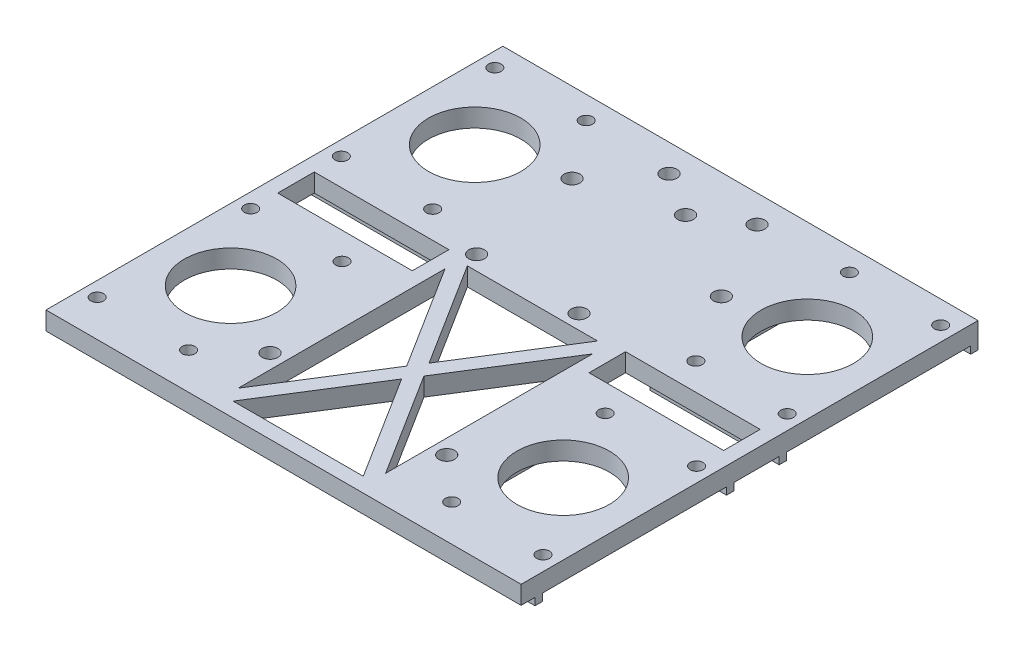
SolidWorks part; units mm, degrees
ref_plane "Front Plane" through (0, 0, 0) normal (0, 0, 1) x (1, 0, 0)
ref_plane "Top Plane" through (0, 0, 0) normal (0, 1, 0) x (1, 0, 0)
ref_plane "Right Plane" through (0, 0, 0) normal (1, 0, 0) x (0, 0, -1)
sketch "Sketch1" plane through (0, 0, 0) normal (0, 1, 0) x (1, 0, 0)
  line L1 (-65, 62.5) -> (65, 62.5)
  line L2 (-65, 62.5) -> (-65, -62.5)
  line L3 (-65, -62.5) -> (65, -62.5)
  line L4 (65, 62.5) -> (65, -62.5)
  line L5 (-65, 62.5) -> (65, -62.5) construction
  line L6 (-65, -62.5) -> (65, 62.5) construction
  point P0 (0, 0)
  dimension "D1" = 130
  dimension "D2" = 125
extrude "Boss-Extrude1" add sketch "Sketch1" along normal blind 5
sketch "Sketch2" plane through (0, 5, 0) normal (0, 1, 0) x (1, 0, 0)
  line L1 (-65, -62.5) -> (65, -62.5) construction
  line L2 (-65, 62.5) -> (-65, -62.5) construction
  circle A0 centre (-61, -52.5) radius 1.75
  circle A1 centre (-36, -52.5) radius 1.75
  circle A2 centre (-36, -10.5) radius 1.75
  circle A3 centre (-61, -10.5) radius 1.75
  circle A4 centre (-45.5, -31.5) radius 12.65
  dimension "D2" = 25.3
  dimension "D7" = 3.5
  dimension "D8" = 3.5
  dimension "D9" = 3.5
  dimension "D10" = 3.5
  dimension "D1" = 19.5
  dimension "D3" = 31
  dimension "D4" = 4
  dimension "D5" = 10
  dimension "D6" = 10
  dimension "D11" = 4
  dimension "D12" = 42
  dimension "D13" = 42
  dimension "D14" = 25
  dimension "D15" = 25
extrude "Cut-Extrude1" cut sketch "Sketch2" against normal blind 10
ref_plane "Plane1" through (0, 0, 0) normal (-1, 0, 0) x (0, 0, 1)
ref_plane "Plane2" through (0, 0, 0) normal (0, 0, 1) x (1, 0, 0)
mirror "Mirror3" about plane through (0, 0, 0) normal (-1, 0, 0) of "Cut-Extrude1"
sketch "Sketch4" plane through (0, 5, 0) normal (0, 1, 0) x (1, 0, 0)
  line L0 (0, 62.5) -> (0, 47.5) construction
  line L1 (65, 62.5) -> (-65, 62.5) construction
  line L2 (-12.0498, 55) -> (12.0498, 55) construction
  circle A0 centre (0, 47.5) radius 2.15
  circle A1 centre (12.0498, 55) radius 2.15
  circle A2 centre (-12.0498, 55) radius 2.15
  point P9 (0, 55)
  dimension "D2" = 4.3
  dimension "D3" = 4.3
  dimension "D4" = 4.3
  dimension "D1" = 15
  dimension "D5" = 24.0996
extrude "Cut-Extrude3" cut sketch "Sketch4" against normal blind 10
sketch "Sketch5" plane through (0, 0, 0) normal (0, -1, 0) x (1, 0, 0)
  line L0 (-58.15, 31.5) -> (-65, 31.5) construction
  line L1 (-65, -62.5) -> (-65, 62.5) construction
  line L2 (-65, 56.7) -> (-65, 6.3)
  line L3 (-65, 56.7) -> (-31.6, 56.7)
  line L4 (-31.6, 56.7) -> (-31.6, 6.3)
  line L5 (-31.6, 6.3) -> (-65, 6.3)
  line L6 (-65, 58.7) -> (-29.6, 58.7)
  line L7 (-29.6, 58.7) -> (-29.6, 4.3)
  line L8 (-29.6, 4.3) -> (-65, 4.3)
  line L9 (-65, 4.3) -> (-65, 6.3)
  line L10 (-65, 58.7) -> (-65, 56.7)
  circle A0 centre (-45.5, 31.5) radius 12.65 construction
  point P10 (-65, 31.5)
  line M39 (-65, 62.5) -> (-65, -62.5)
  dimension "D1" = 50.4
  dimension "D2" = 33.4
  dimension "D3" = 2
  dimension "D4" = 2
  dimension "D5" = 2
extrude "Boss-Extrude2" add sketch "Sketch5" along normal blind 2 contours L8 L7 L6 L3 L4 L5 M39
mirror "Mirror5" about plane through (0, 0, 0) normal (-1, 0, 0) of "Boss-Extrude2"
ref_plane "Plane3" through (0, 0, 0) normal (0, 0, 1) x (1, 0, 0)
ref_plane "Plane4" through (0, 0, -1.9) normal (0, 0, 1) x (1, 0, 0)
mirror "Mirror7" about plane through (0, 0, -1.9) normal (0, 0, 1) of "Mirror5", "Boss-Extrude2", "Mirror3", "Cut-Extrude1"
ref_plane "Plane5" through (0, 0, 0) normal (0, -1, 0) x (-1, 0, 0)
sketch "Sketch10" plane through (0, 0, 0) normal (0, -1, 0) x (-1, 0, 0)
  circle A0 centre (-24.17, -42.03) radius 2.15
  circle A1 centre (24.17, -42.03) radius 2.15
  circle A2 centre (-8.73, 9.6) radius 2.15
  circle A3 centre (19.29, 9.6) radius 2.15
  circle A4 centre (-24.17, 33.11) radius 2.15
  circle A5 centre (24.17, 40.6) radius 2.15
  dimension "D1" = 4.3
  dimension "D6" = 4.3
  dimension "D7" = 4.3
  dimension "D10" = 4.3
  dimension "D11" = 4.3
  dimension "D12" = 4.3
extrude "Cut-Extrude8" cut sketch "Sketch10" against normal through all
sketch "Sketch11" plane through (0, 0, 0) normal (0, -1, 0) x (1, 0, 0)
  circle A0 centre (-12.0498, -55) radius 2.65
  circle A1 centre (0, -47.5) radius 2.65
  circle A2 centre (12.0498, -55) radius 2.65
  circle A3 centre (-24.17, -40.6) radius 2.65
  circle A4 centre (24.17, -33.11) radius 2.65
  circle A5 centre (8.73, -9.6) radius 2.65
  circle A6 centre (-19.29, -9.6) radius 2.65
  circle A7 centre (-24.17, 42.03) radius 2.65
  circle A8 centre (24.17, 42.03) radius 2.65
  circle A9 centre (-61, -14.3) radius 2.65
  circle A10 centre (-36, -14.3) radius 2.65
  circle A11 centre (-61, -56.3) radius 2.65
  circle A12 centre (-36, -56.3) radius 2.65
  circle A13 centre (36, -56.3) radius 2.65
  circle A14 centre (61, -56.3) radius 2.65
  circle A15 centre (36, -14.3) radius 2.65
  circle A16 centre (61, -14.3) radius 2.65
  circle A17 centre (36, 10.5) radius 2.65
  circle A18 centre (61, 10.5) radius 2.65
  circle A19 centre (61, 52.5) radius 2.65
  circle A20 centre (36, 52.5) radius 2.65
  circle A21 centre (-36, 52.5) radius 2.65
  circle A22 centre (-36, 10.5) radius 2.65
  circle A23 centre (-61, 10.5) radius 2.65
  circle A24 centre (-61, 52.5) radius 2.65
  dimension "D1" = 5.3
  dimension "D2" = 5.3
  dimension "D3" = 5.3
  dimension "D4" = 5.3
  dimension "D5" = 5.3
  dimension "D6" = 5.3
  dimension "D7" = 5.3
  dimension "D8" = 5.3
  dimension "D9" = 5.3
  dimension "D10" = 5.3
  dimension "D11" = 5.3
  dimension "D12" = 5.3
  dimension "D13" = 5.3
  dimension "D14" = 5.3
  dimension "D15" = 5.3
  dimension "D16" = 5.3
  dimension "D17" = 5.3
  dimension "D18" = 5.3
  dimension "D19" = 5.3
  dimension "D20" = 5.3
  dimension "D21" = 5.3
  dimension "D22" = 5.3
  dimension "D23" = 5.3
  dimension "D24" = 5.3
  dimension "D25" = 5.3
extrude "Cut-Extrude9" cut sketch "Sketch11" against normal blind 0.5
sketch "Sketch12" plane through (0, 5, 0) normal (0, 1, 0) x (1, 0, 0)
  line L0 (-65, -62.5) -> (65, -62.5) construction
  line L1 (-20.17, 5.6) -> (20.17, 5.6)
  line L2 (-20.17, 5.6) -> (-20.17, -58.5)
  line L3 (-20.17, -58.5) -> (20.17, -58.5)
  line L4 (20.17, 5.6) -> (20.17, -58.5)
  line L5 (-20.17, 5.6) -> (20.17, -58.5) construction
  line L6 (-20.17, -58.5) -> (20.17, 5.6) construction
  line L7 (-17.8069, 5.6) -> (0, -22.6951)
  line L8 (20.17, -54.7451) -> (2.3631, -26.45)
  line L9 (2.3631, -26.45) -> (20.17, 1.8451)
  line L10 (0, -22.6951) -> (17.8069, 5.6)
  line L11 (-20.17, 1.8451) -> (-2.3631, -26.45)
  line L12 (-2.3631, -26.45) -> (-20.17, -54.7451)
  line L13 (-17.8069, -58.5) -> (0, -30.2049)
  line L14 (0, -30.2049) -> (17.8069, -58.5)
  circle A0 centre (-19.29, 9.6) radius 2.15 construction
  circle A1 centre (-24.17, -42.03) radius 2.15 construction
  circle A2 centre (24.17, -42.03) radius 2.15 construction
  dimension "D2" = 4
  dimension "D3" = 4
  dimension "D1" = 4
  dimension "D4" = 4
  dimension "D5" = 2
  dimension "D6" = 2
  dimension "D7" = 2
  dimension "D8" = 2
extrude "Cut-Extrude10" cut sketch "Sketch12" against normal through all contours L12 L11 L2 | L7 L10 L1 | L9 L8 L4 | L14 L13 L3
sketch "Sketch13" plane through (0, 5, 0) normal (0, 1, 0) x (1, 0, 0)
  line L0 (-61, 14.3) -> (-61, -10.5) construction
  line L1 (-61, 1.9) -> (-61, -3.1)
  line L2 (-61, -3.1) -> (-24.17, -3.1)
  line L3 (-24.17, -3.1) -> (-24.17, 6.9)
  line L4 (-24.17, 6.9) -> (-61, 6.9)
  line L5 (-61, 6.9) -> (-61, 1.9)
  line L6 (-20.17, 1.8451) -> (-20.17, -54.7451) construction
  dimension "D1" = 10
  dimension "D2" = 5
  dimension "D3" = 4
extrude "Cut-Extrude11" cut sketch "Sketch13" against normal through all
mirror "Mirror9" about plane through (0, 0, 0) normal (-1, 0, 0) of "Cut-Extrude11"
